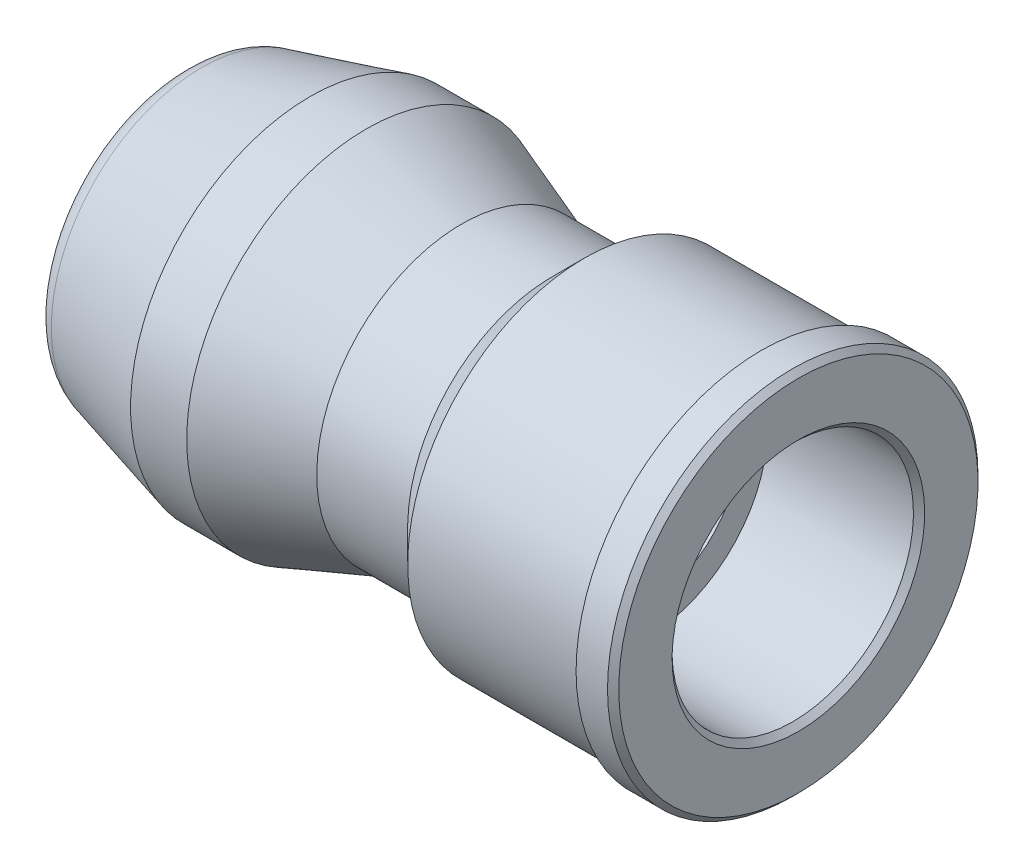
SolidWorks part; units mm, degrees
material "Nikel gümüş 65-12, UNS C75700"
ref_plane "Ön Düzlem" through (0, 0, 0) normal (0, 0, 1) x (1, 0, 0)
ref_plane "Üst Düzlem" through (0, 0, 0) normal (0, 1, 0) x (1, 0, 0)
ref_plane "Sağ Düzlem" through (0, 0, 0) normal (1, 0, 0) x (0, 0, -1)
sketch "Çizim1" plane through (0, 0, 0) normal (0, 0, 1) x (1, 0, 0)
  line L1 (0, 0) -> (0, 2.58)
  line L2 (0, 2.58) -> (2.3, 3.1963)
  line L3 (2.3, 3.1963) -> (3.3, 3.1963)
  line L4 (3.3, 3.1963) -> (5, 2.58)
  line L5 (5, 2.58) -> (6.62, 2.58)
  line L6 (6.62, 2.58) -> (7.19, 3.15)
  line L7 (7.19, 3.15) -> (10.34, 3.15)
  line L11 (10.34, 3.15) -> (10.34, 3.3)
  line L12 (10.34, 3.3) -> (11, 3.3)
  line L13 (11, 3.3) -> (11, 2.15)
  line L14 (11, 2.15) -> (8.3, 2.15)
  line L15 (8.3, 2.15) -> (8.3, 0)
  line L17 (0, 0) -> (8.3, 0)
  dimension "D1" = 8.3
  dimension "D2" = 105
  dimension "D3" = 2.58
  dimension "D4" = 2.3
  dimension "D5" = 1.7
  dimension "D6" = 135
  dimension "D7" = 1
  dimension "D8" = 1.62
  dimension "D9" = 2.15
  dimension "D10" = 2.7
  dimension "D11" = 1.15
  dimension "D12" = 1
  dimension "D13" = 3.15
revolve "Döndür1" add sketch "Çizim1" angle 360 about L17
hole_wizard "M4 Dişli Delik2" positions "Çizim4" profile "Çizim6" tap size "M4" standard "ISO" end condition through all
sketch "Çizim4" plane through (0, 0, 0) normal (-1, 0, 0) x (0, 0, 1)
  point P0 (0, 0)
sketch "Çizim6" plane through (0, 0, 0) normal (0, 1, 0) x (0, 0, 1)
  line L0 (0, 0) -> (0, 11)
  line L1 (0, 11) -> (1.65, 11)
  line L2 (1.65, 11) -> (1.65, 0.9053)
  line L3 (1.65, 0.9053) -> (2.025, 0)
  line L5 (2.025, 0) -> (0, 0)
  line L6 (-1.65, 0.9053) -> (-2.025, 0) construction
  line L11 (0, -6.35) -> (0, 107.95) construction
  dimension "Thru Tap Drill Dia." = 3.3
  dimension "Thru Tap Drill Depth" = 11
  dimension "Near C'Sink Dia." = 4.05
  dimension "Near C'Sink Angle" = 45
cosmetic thread "Delik Dişi2" parameters "D2"=4
fillet "Radyus1" radius 0.1 3 edges at (11, -3.3, 0) (11, -2.15, 0) (10.34, -3.15, 0) profile chamfer
fillet "Radyus2" radius 0.5 1 edges at (0, -2.58, 0)
